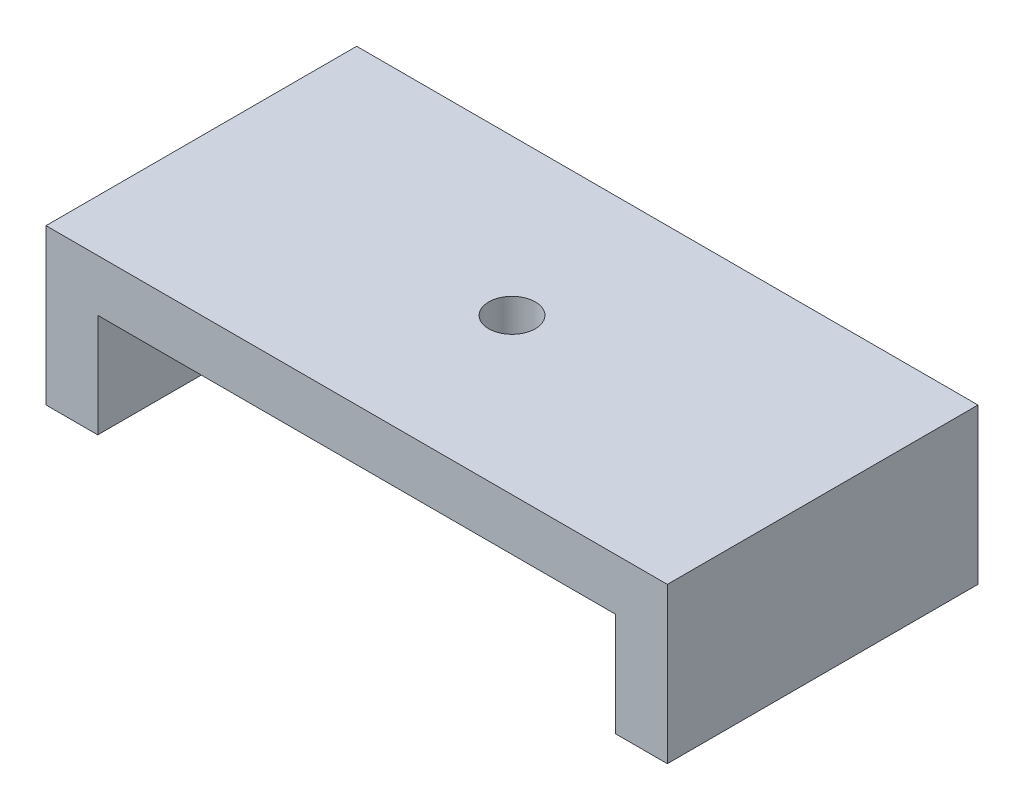
SolidWorks part; units mm, degrees
ref_plane "Front Plane" through (0, 0, 0) normal (0, 0, 1) x (1, 0, 0)
ref_plane "Top Plane" through (0, 0, 0) normal (0, 1, 0) x (1, 0, 0)
ref_plane "Right Plane" through (0, 0, 0) normal (1, 0, 0) x (0, 0, -1)
sketch "Sketch1" plane through (0, 0, 0) normal (0, 0, 1) x (1, 0, 0)
  line L0 (0, 0) -> (60, 0)
  line L1 (60, 0) -> (60, -15)
  line L2 (60, -15) -> (55, -15)
  line L3 (55, -15) -> (55, -5)
  line L4 (55, -5) -> (5, -5)
  line L5 (5, -5) -> (5, -15)
  line L6 (5, -15) -> (0, -15)
  line L7 (0, -15) -> (0, 0)
  dimension "D1" = 60
  dimension "D2" = 15
  dimension "D3" = 5
  dimension "D4" = 15
  dimension "D5" = 5
  dimension "D6" = 5
extrude "Boss-Extrude1" add sketch "Sketch1" along normal blind 30
sketch "Sketch2" plane through (0, 0, 0) normal (0, 1, 0) x (1, 0, 0)
  line L0 (60, -30) -> (0, -30) construction
  line L1 (60, -30) -> (60, 0) construction
  circle A0 centre (30, -15) radius 2.25
  point P4 (30, -30)
  point P7 (60, -15)
  dimension "D1" = 4.5
extrude "Cut-Extrude1" cut sketch "Sketch2" against normal through all
